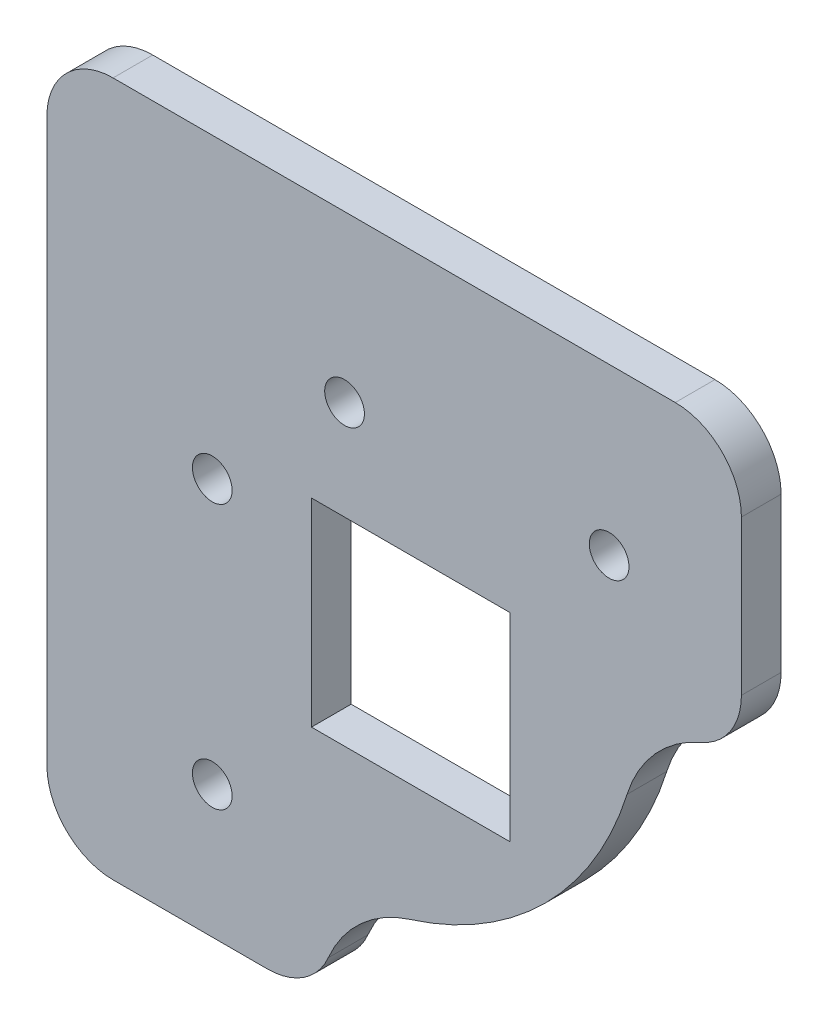
SolidWorks part; units mm, degrees
material "Thornel Mat VMA"
ref_plane "前视基准面" through (0, 0, 0) normal (0, 0, 1) x (1, 0, 0)
ref_plane "上视基准面" through (0, 0, 0) normal (0, 1, 0) x (1, 0, 0)
ref_plane "右视基准面" through (0, 0, 0) normal (1, 0, 0) x (0, 0, -1)
sketch "草图1" plane through (0, 0, 0) normal (0, 0, 1) x (1, 0, 0)
  line L0 (0, 0) -> (52.5, 0)
  line L1 (52.5, 0) -> (52.5, -20.5)
  line L5 (20.5, -52.5) -> (0, -52.5)
  line L6 (0, -52.5) -> (0, 0)
  line L7 (12.5, -12.5) -> (12.5, -52.5) construction
  line L8 (12.5, -12.5) -> (52.5, -12.5) construction
  line L9 (0, 0) -> (20, -20) construction
  line L10 (20, -20) -> (35, -20)
  line L11 (20, -20) -> (20, -35)
  line L12 (20, -35) -> (35, -35)
  line L13 (35, -20) -> (35, -35)
  circle A0 centre (22.5, -12.5) radius 1.5
  circle A1 centre (42.5, -12.5) radius 1.5
  arc A2 (43.8576, -27.471) -> (27.471, -43.8576) centre (20, -20) cw
  circle A3 centre (12.5, -42.5) radius 1.5
  circle A5 centre (12.5, -22.5) radius 1.5
  arc A6 (20.5, -52.5) -> (27.471, -43.8576) centre (30.4594, -53.4006) cw
  arc A7 (52.5, -20.5) -> (43.8576, -27.471) centre (53.4006, -30.4594) ccw
  dimension "D12" = 3
  dimension "D13" = 10
  dimension "D15" = 10
  dimension "D6" = 25
  dimension "D7" = 40
  dimension "D9" = 20
  dimension "D1" = 12.5
  dimension "D2" = 12.5
  dimension "D3" = 20
  dimension "D4" = 20
  dimension "D5" = 15
  dimension "D8" = 8
extrude "凸台-拉伸1" add sketch "草图1" along normal blind 3
fillet "圆角1" radius 5 5 edges at (52.5, -20.5, 1.5) (52.5, 0, 1.5) (0, 0, 1.5) (0, -52.5, 1.5) (20.5, -52.5, 1.5)
